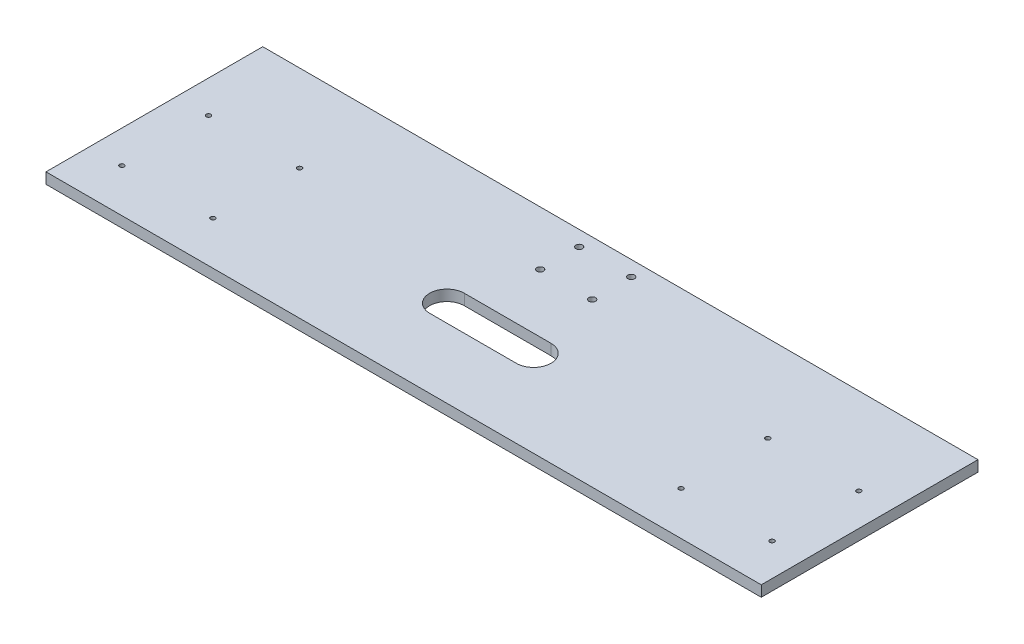
SolidWorks part; units mm, degrees
ref_plane "前视基准面" through (0, 0, 0) normal (0, 0, 1) x (1, 0, 0)
ref_plane "上视基准面" through (0, 0, 0) normal (0, 1, 0) x (1, 0, 0)
ref_plane "右视基准面" through (0, 0, 0) normal (1, 0, 0) x (0, 0, -1)
sketch "草图1" plane through (0, 0, 0) normal (0, 1, 0) x (1, 0, 0)
  line L1 (-155.3696, -90.2724) -> (174.6304, -90.2724)
  line L2 (-155.3696, -90.2724) -> (-155.3696, -190.2724)
  line L3 (-155.3696, -190.2724) -> (174.6304, -190.2724)
  line L4 (174.6304, -90.2724) -> (174.6304, -190.2724)
  dimension "D1" = 330
  dimension "D2" = 100
extrude "凸台-拉伸1" add sketch "草图1" along normal blind 5
sketch "草图3" plane through (0, 5, 0) normal (0, 1, 0) x (1, 0, 0)
  line L0 (9.6304, -73.8743) -> (9.6304, -261.3849) construction
  line L1 (-2.3696, -97.2724) -> (-2.3696, -133.7579) construction
  line L2 (174.6304, -90.2724) -> (-155.3696, -90.2724) construction
  circle A0 centre (-2.3696, -97.2724) radius 1.515
  circle A1 centre (21.6304, -97.2724) radius 1.515
  circle A2 centre (-2.3696, -115.2724) radius 1.515
  circle A3 centre (21.6304, -115.2724) radius 1.515
  point P13 (9.6304, -90.2724)
  dimension "D1" = 3.03
  dimension "D2" = 24
  dimension "D3" = 18
  dimension "D4" = 18
  dimension "D5" = 24
  dimension "D6" = 7
extrude "切除-拉伸1" cut sketch "草图3" against normal through all
sketch "草图4" plane through (0, 5, 0) normal (0, 1, 0) x (1, 0, 0)
  line L0 (-155.3696, -150.2724) -> (174.6304, -150.2724) construction
  line L1 (-155.3696, -90.2724) -> (-155.3696, -190.2724) construction
  line L2 (174.6304, -190.2724) -> (174.6304, -90.2724) construction
  line L3 (9.6304, -149.3208) -> (9.6304, -90.2724) construction
  line L4 (-10.3696, -150.2724) -> (29.6304, -150.2724) construction
  line L5 (-155.3696, -190.2724) -> (174.6304, -190.2724) construction
  line L6 (-10.3696, -142.2724) -> (29.6304, -142.2724)
  line L7 (-10.3696, -158.2724) -> (29.6304, -158.2724)
  circle A0 centre (-140.3696, -170.2724) radius 1.05
  circle A1 centre (-140.3696, -130.2724) radius 1.05
  circle A2 centre (-98.3696, -170.2724) radius 1.05
  circle A3 centre (-98.3696, -130.2724) radius 1.05
  circle A4 centre (117.6304, -130.2724) radius 1.05
  circle A5 centre (117.6304, -170.2724) radius 1.05
  circle A6 centre (159.6304, -130.2724) radius 1.05
  circle A7 centre (159.6304, -170.2724) radius 1.05
  arc A8 (-10.3696, -142.2724) -> (-10.3696, -158.2724) centre (-10.3696, -150.2724) ccw
  arc A9 (29.6304, -158.2724) -> (29.6304, -142.2724) centre (29.6304, -150.2724) ccw
  point P28 (9.6304, -150.2724)
  point P33 (9.6304, -150.2724)
  dimension "D1" = 2.1
  dimension "D3" = 42
  dimension "D8" = 8
  dimension "D2" = 20
  dimension "D4" = 15
  dimension "D5" = 40
  dimension "D6" = 20
  dimension "D7" = 20
extrude "切除-拉伸2" cut sketch "草图4" against normal through all
